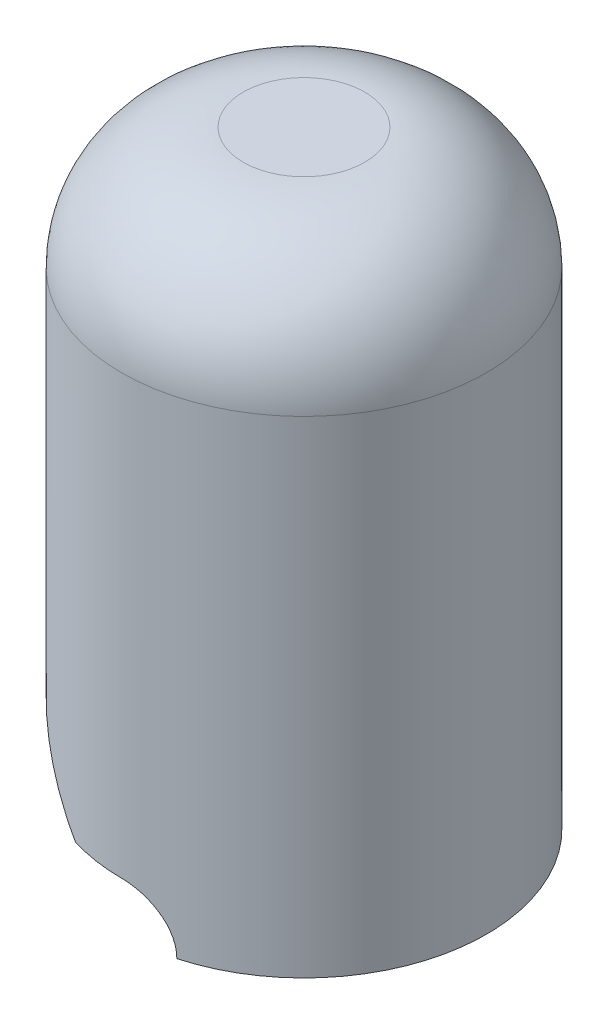
SolidWorks part; units mm, degrees
ref_plane "Alzado" through (0, 0, 0) normal (0, 0, 1) x (1, 0, 0)
ref_plane "Planta" through (0, 0, 0) normal (0, 1, 0) x (1, 0, 0)
ref_plane "Vista lateral" through (0, 0, 0) normal (1, 0, 0) x (0, 0, -1)
sketch "Croquis1" plane through (0, 0, 0) normal (0, 1, 0) x (1, 0, 0)
  circle A0 centre (0, 0) radius 15
  dimension "D1" = 30
extrude "Saliente-Extruir1" add sketch "Croquis1" along normal blind 50 contours A0
sketch "Croquis2" plane through (0, 0, 0) normal (0, 0, 1) x (1, 0, 0)
  circle A0 centre (0, 0) radius 4
  dimension "D1" = 8
extrude "Saliente-Extruir2" add sketch "Croquis2" along normal mid plane 15
sketch "Croquis3" plane through (0, 0, 7.5) normal (0, 0, 1) x (1, 0, 0)
  circle A0 centre (0, 0) radius 4
extrude "Cortar-Extruir2" cut sketch "Croquis3" along normal blind 8
mirror "Simetría1" about plane through (0, 0, 0) normal (0, 0, 1) of "Cortar-Extruir2"
fillet "Redondeo1" radius 10 1 edges at (0, 50, 15)
sketch "Croquis4" plane through (0, 0, 0) normal (0, 0, 1) x (1, 0, 0)
  line L0 (0, 0) -> (-15, 13.3765) construction
  line L1 (-15, 40) -> (-15, 0) construction
  line L2 (-15, 13.3765) -> (-15, 0)
  line L3 (-15, 0) -> (-4, 0) construction
  line L4 (-15, 0) -> (-4, 0)
  line L5 (-4, 0) -> (-4, 3.5671)
  line L6 (-4, 3.5671) -> (-15, 13.3765)
  dimension "D1" = 131.725
extrude "Cortar-Extruir3" cut sketch "Croquis4" against normal mid plane 30
sketch "Croquis5" plane through (0, 0, 0) normal (0, 0, 1) x (1, 0, 0)
  line L0 (0, 4) -> (-7.9072, 4)
  line L1 (-7.9072, 4) -> (-7.9072, -4)
  line L2 (-7.9072, -4) -> (0, -4)
  arc A0 (4, 0) -> (-4, 0) centre (0, 0) ccw construction
  arc A1 (-4, 0) -> (4, 0) centre (0, 0) ccw construction
  arc A2 (0, 4) -> (0, -4) centre (0, 0) ccw
extrude "Cortar-Extruir4" cut sketch "Croquis5" against normal mid plane 30
sketch "Croquis6" plane through (0, 0, 7.5) normal (0, 0, 1) x (1, 0, 0)
  circle A0 centre (0, 0) radius 2.5
  dimension "D1" = 5
extrude "Cortar-Extruir5" cut sketch "Croquis6" against normal blind 15
